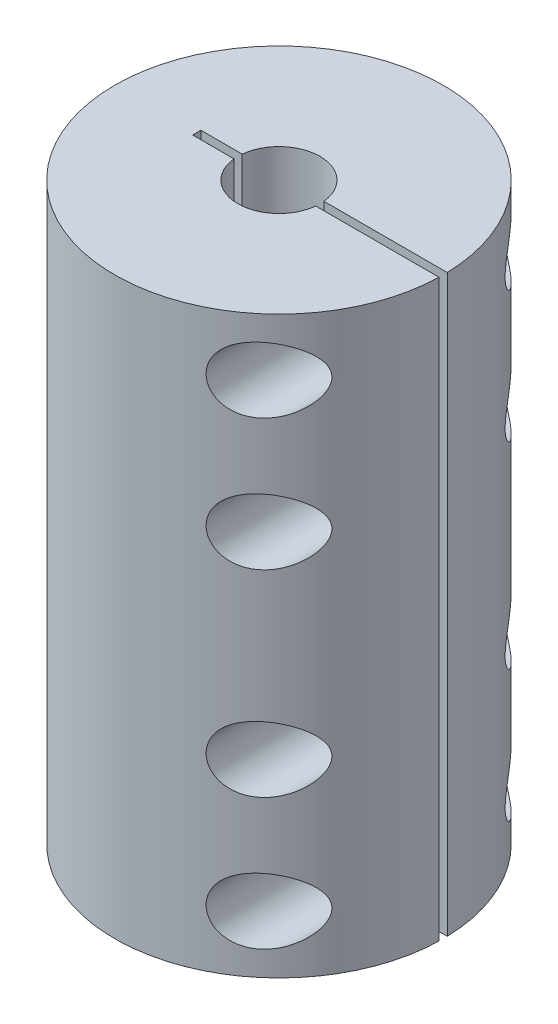
SolidWorks part; units mm, degrees
ref_plane "Front Plane" through (0, 0, 0) normal (0, 0, 1) x (1, 0, 0)
ref_plane "Top Plane" through (0, 0, 0) normal (0, 1, 0) x (1, 0, 0)
ref_plane "Right Plane" through (0, 0, 0) normal (1, 0, 0) x (0, 0, -1)
sketch "Sketch1" plane through (0, 0, 0) normal (0, 1, 0) x (1, 0, 0)
  circle A0 centre (0, 0) radius 10
  dimension "D1" = 20
extrude "Boss-Extrude1" add sketch "Sketch1" along normal blind 35
sketch "Sketch2" plane through (0, 35, 0) normal (0, 1, 0) x (1, 0, 0)
  circle A0 centre (0, 0) radius 2.5
  dimension "D1" = 5
extrude "Cut-Extrude1" cut sketch "Sketch2" against normal through all both and the other way through all
sketch "Sketch3" plane through (0, 0, 0) normal (0, -1, 0) x (1, 0, 0)
  circle A0 centre (0, 0) radius 4
  dimension "D1" = 8
extrude "Cut-Extrude2" cut sketch "Sketch3" against normal blind 17.5
sketch "Sketch4" plane through (0, 0, 0) normal (0, -1, 0) x (1, 0, 0)
  line L1 (-5, 0.25) -> (10, 0.25)
  line L2 (-5, 0.25) -> (-5, -0.25)
  line L3 (-5, -0.25) -> (10, -0.25)
  line L4 (10, 0.25) -> (10, -0.25)
  point P4 (-5, 0)
  point P6 (-6.0315, -0.25)
  dimension "D1" = 0.5
  dimension "D2" = 15
  dimension "D3" = 5
extrude "Cut-Extrude3" cut sketch "Sketch4" against normal through all both and the other way through all
sketch "Sketch5" plane through (0, 0, 0) normal (0, 0, 1) x (1, 0, 0)
  line L0 (9.9969, 35) -> (2.4875, 35) construction
  line L2 (9.9969, 0) -> (9.9969, 35) construction
  line L3 (-10, 0) -> (9.9969, 0) construction
  circle A0 centre (6.4969, 31.5) radius 2
  circle A1 centre (6.4969, 23.5) radius 2
  circle A2 centre (6.4969, 11.5) radius 2
  circle A3 centre (6.4969, 3.5) radius 2
  point P8 (6.7852, 31.4977)
  point P13 (9.9969, 30.5786)
  point P14 (0, 0)
  dimension "D1" = 4
  dimension "D3" = 3.5
  dimension "D4" = 8
  dimension "D5" = 3.5
  dimension "D6" = 8
  dimension "D2" = 3.5
extrude "Cut-Extrude4" cut sketch "Sketch5" against normal through all both and the other way through all
